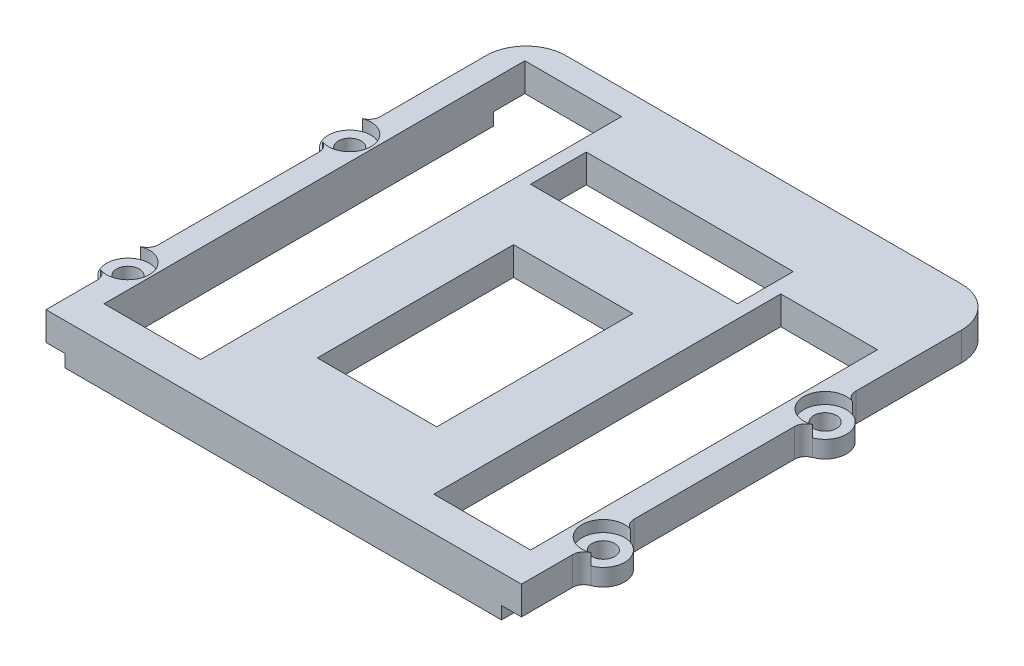
SolidWorks part; units mm, degrees
ref_plane "Front Plane" through (0, 0, 0) normal (0, 0, 1) x (1, 0, 0)
ref_plane "Top Plane" through (0, 0, 0) normal (0, 1, 0) x (1, 0, 0)
ref_plane "Right Plane" through (0, 0, 0) normal (1, 0, 0) x (0, 0, -1)
sketch "Sketch1" plane through (0, 0, 0) normal (0, 1, 0) x (1, 0, 0)
  line L0 (-66, 42.75) -> (66, 42.75)
  line L1 (-66, 42.75) -> (-66, -42.75)
  line L2 (-66, -42.75) -> (66, -42.75)
  line L3 (66, 42.75) -> (66, -42.75)
extrude "Boss-Extrude1" add sketch "Sketch1" along normal blind 5
sketch "Sketch4" plane through (0, 5, 0) normal (0, 1, 0) x (1, 0, 0)
  line L0 (-66, -7.75) -> (66, -7.75) construction
  line L3 (0, 42.75) -> (0, -42.75) construction
  line L4 (-66, 42.75) -> (66, 42.75) construction
  line L5 (-66, -42.75) -> (66, -42.75) construction
  line L6 (-66, 15.5) -> (-66, 8)
  line L7 (-66, -23.5) -> (-66, -31)
  line L8 (66, -31) -> (66, -23.5)
  line L9 (66, 8) -> (66, 15.5)
  arc A0 (-66, 15.5) -> (-66, 8) centre (-66, 11.75) ccw
  arc A1 (-66, -31) -> (-66, -23.5) centre (-66, -27.25) cw
  arc A2 (66, 15.5) -> (66, 8) centre (66, 11.75) cw
  arc A3 (66, -31) -> (66, -23.5) centre (66, -27.25) ccw
  dimension "D1" = 35
  dimension "D2" = 19.5
extrude "Boss-Extrude3" add sketch "Sketch4" against normal up to surface (5 mm away) up to face at (0, 0, 0)
fillet "Fillet1" radius 2 8 edges at (-66, 2.5, -8) (-66, 2.5, -15.5) (-66, 2.5, 31) (-66, 2.5, 23.5) (66, 2.5, 23.5) (66, 2.5, 31) (66, 2.5, -15.5) (66, 2.5, -8)
sketch "Sketch5" plane through (0, 5, 0) normal (0, 1, 0) x (1, 0, 0)
  circle A0 centre (-66, 11.75) radius 2
  circle A1 centre (66, 11.75) radius 2
  circle A2 centre (66, -27.25) radius 2
  circle A3 centre (-66, -27.25) radius 2
extrude "Cut-Extrude1" cut sketch "Sketch5" against normal blind 7
sketch "Sketch6" plane through (0, 5, 0) normal (0, 1, 0) x (1, 0, 0)
  circle A0 centre (-66, 11.75) radius 3.75
  circle A1 centre (-66, -27.25) radius 3.75
  circle A2 centre (66, -27.25) radius 3.75
  circle A3 centre (66, 11.75) radius 3.75
  dimension "D1" = 7.5
extrude "Cut-Extrude2" cut sketch "Sketch6" against normal blind 2
fillet "Fillet2" radius 7 2 edges at (66, 2.5, -42.75) (-66, 2.5, -42.75)
sketch "Sketch7" plane through (0, 0, 42.75) normal (0, 0, 1) x (1, 0, 0)
  line L0 (-24.2, -24) -> (-24.2, 15.2076) construction
  line L3 (-24.2, 15.2076) -> (77.4528, 15.2076)
  line L4 (-24.2, 15.2076) -> (-24.2, -6.5862)
  line L5 (-24.2, -6.5862) -> (77.4528, -6.5862)
  line L6 (77.4528, 15.2076) -> (77.4528, -6.5862)
extrude "Cut-Extrude3" cut sketch "Sketch7" against normal blind 90
mirror "Mirror1" about plane through (-24.2, 15.2076, -47.25) normal (-1, 0, 0) of bodies 106
sketch "Sketch9" plane through (0, 5, 0) normal (0, 1, 0) x (1, 0, 0)
  line L0 (-44.8, -26.35) -> (-44.8, 38.35)
  line L1 (-61.8, 38.35) -> (-61.8, -26.35)
  line L2 (-44.8, 38.35) -> (-61.8, 38.35)
  line L3 (-61.8, -35.65) -> (-61.8, -26.35)
  line L4 (-44.8, -26.35) -> (-44.8, -35.65)
  line L5 (-44.8, -35.65) -> (-61.8, -35.65)
  line L6 (-34.8, -25.15) -> (-23.1, -25.15)
  line L7 (-34.8, -8.65) -> (-34.8, -25.15)
  line L8 (-13.8, 9.35) -> (-23.1, 9.35)
  line L9 (-13.8, -8.65) -> (-13.8, 9.35)
  line L10 (13.2, -26.35) -> (13.2, -35.65)
  line L11 (13.2, -35.65) -> (-3.8, -35.65)
  line L12 (-3.8, -35.65) -> (-3.8, -26.35)
  line L13 (-3.8, 25.35) -> (13.2, 25.35)
  line L14 (13.2, 25.35) -> (13.2, -26.35)
  line L15 (-3.8, -26.35) -> (-3.8, 25.35)
  line L16 (-22.6, 29.85) -> (-42.5, 29.85)
  line L17 (-42.5, 29.85) -> (-42.5, 20.05)
  line L18 (-6.1, 20.05) -> (-42.5, 20.05)
  line L19 (-34.8, -8.65) -> (-34.8, 9.35)
  line L20 (-34.8, 9.35) -> (-23.1, 9.35)
  line L21 (-23.1, -25.15) -> (-13.8, -25.15)
  line L22 (-13.8, -25.15) -> (-13.8, -8.65)
  line L23 (-6.1, 29.85) -> (-22.6, 29.85)
  line L24 (-6.1, 20.05) -> (-6.1, 29.85)
  point P0 (-66, 23)
extrude "Cut-Extrude4" cut sketch "Sketch9" against normal up to surface (5 mm away) up to face at (-66, 0, 29.25)
sketch "Sketch11" plane through (0, 0, 0) normal (0, -1, 0) x (1, 0, 0)
  line L1 (14.1, 42.75) -> (-62.7, 42.75)
  line L4 (-62.7, 42.75) -> (-62.7, -32.8106)
  line L6 (14.1, -32.8106) -> (14.1, 42.75)
  line L7 (-61.8, 40.2501) -> (-61.8, -32.8106)
  line L8 (13.2, -32.8106) -> (13.2, 40.2501)
  line L9 (-62.7, -32.8106) -> (-61.8, -32.8106)
  line L10 (13.2, -32.8106) -> (14.1, -32.8106)
  line L11 (-61.8, 40.2501) -> (13.2, 40.2501)
extrude "Boss-Extrude4" add sketch "Sketch11" along normal blind 2.2
sketch "Sketch12" plane through (0, 0, 42.75) normal (0, 0, 1) x (1, 0, 0)
  line L8 (-66, 0) -> (-62.7, 0)
  line L9 (-62.7, 0) -> (-62.7, -2.2)
  line L10 (-62.7, -2.2) -> (14.1, -2.2)
  line L11 (14.1, -2.2) -> (14.1, 0)
  line L12 (14.1, 0) -> (17.6, 0)
  line L13 (17.6, 0) -> (17.6, 5)
  line L14 (17.6, 5) -> (-66, 5)
  line L15 (-66, 5) -> (-66, 0)
  line L16 (-66, 0) -> (-62.7, 0)
  line L17 (-62.7, 0) -> (-62.7, -2.2)
  line L18 (-62.7, -2.2) -> (14.1, -2.2)
  line L19 (14.1, -2.2) -> (14.1, 0)
  line L20 (14.1, 0) -> (17.6, 0)
  line L21 (17.6, 0) -> (17.6, 5)
  line L22 (17.6, 5) -> (-66, 5)
  line L23 (-66, 5) -> (-66, 0)
  dimension "D1" = 0
extrude "Cut-Extrude5" cut sketch "Sketch12" against normal blind 1.1
